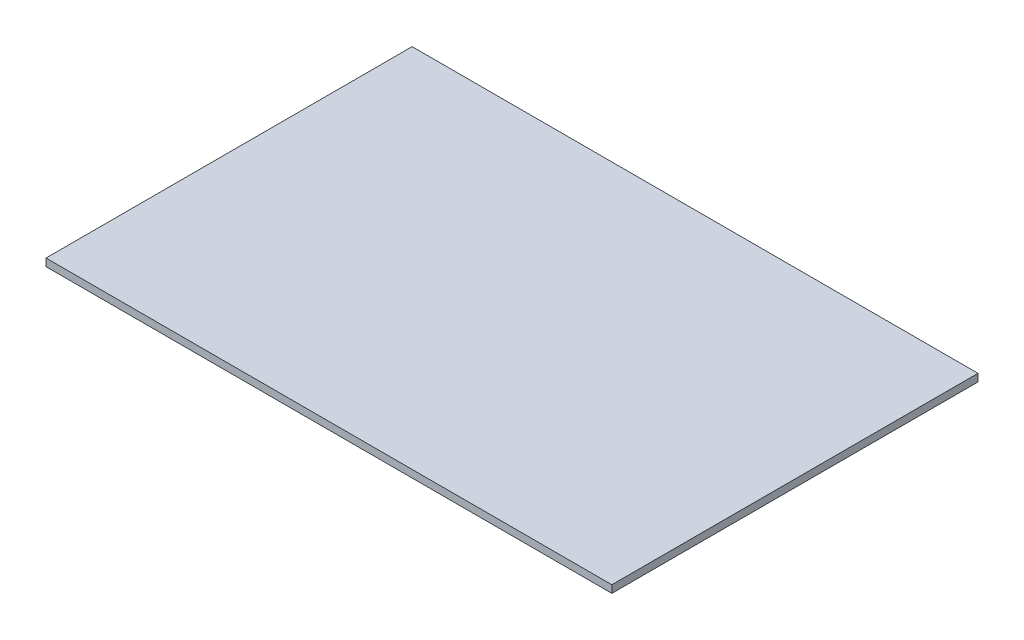
SolidWorks part; units mm, degrees
material "ABS PC"
ref_plane "Front Plane" through (0, 0, 0) normal (0, 0, 1) x (1, 0, 0)
ref_plane "Top Plane" through (0, 0, 0) normal (0, 1, 0) x (1, 0, 0)
ref_plane "Right Plane" through (0, 0, 0) normal (1, 0, 0) x (0, 0, -1)
sketch "Sketch1" plane through (0, 0, 0) normal (0, 1, 0) x (1, 0, 0)
  line L0 (-85, 55) -> (85, -55) construction
  line L1 (-85, 55) -> (85, 55)
  line L2 (-85, 55) -> (-85, -55)
  line L3 (-85, -55) -> (85, -55)
  line L4 (85, 55) -> (85, -55)
  dimension "D1" = 110
  dimension "D2" = 170
extrude "Boss-Extrude1" add sketch "Sketch1" along normal blind 2.25
